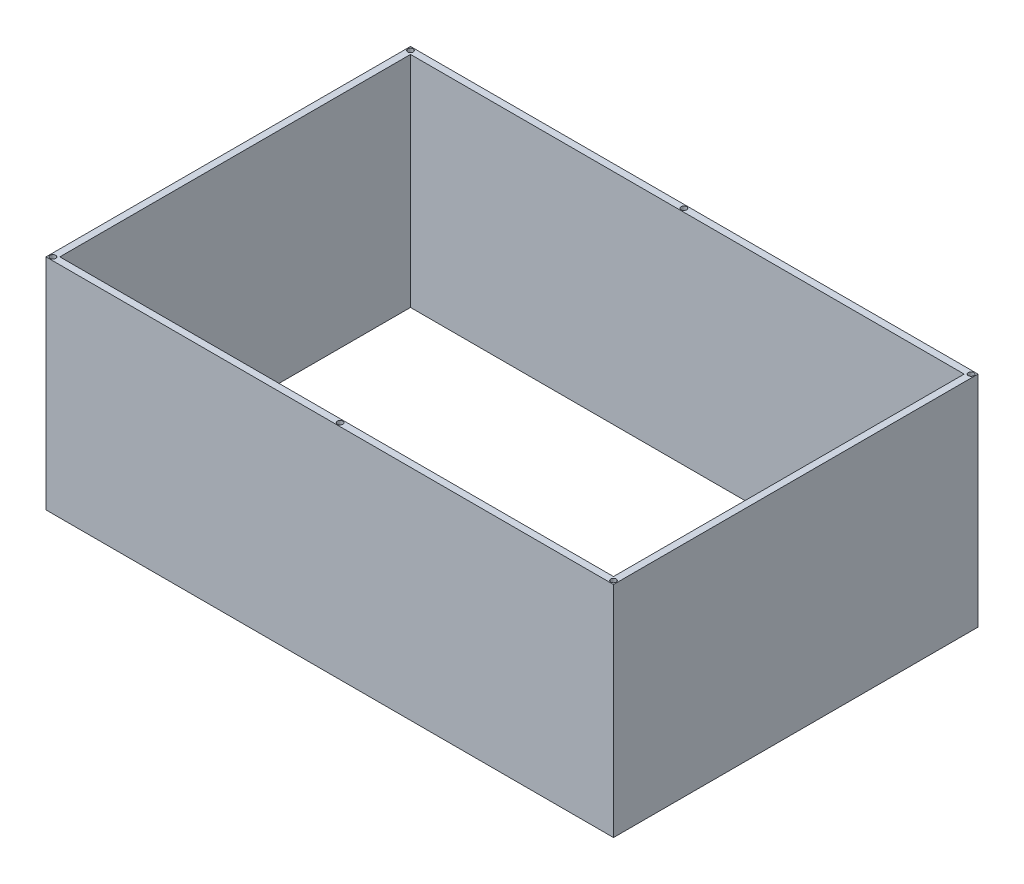
SolidWorks part; units mm, degrees
material "6061-T6 (SS)"
ref_plane "Front Plane" through (0, 0, 0) normal (0, 0, 1) x (1, 0, 0)
ref_plane "Top Plane" through (0, 0, 0) normal (0, 1, 0) x (1, 0, 0)
ref_plane "Right Plane" through (0, 0, 0) normal (1, 0, 0) x (0, 0, -1)
sketch "Sketch5" plane through (0, 0, 0) normal (0, 1, 0) x (1, 0, 0)
  line L0 (-123, 79) -> (-123, -79)
  line L1 (-120, 76) -> (120, 76)
  line L2 (-120, 76) -> (-120, -76)
  line L3 (-120, -76) -> (120, -76)
  line L4 (120, 76) -> (120, -76)
  line L7 (-123, -79) -> (123, -79)
  line L8 (123, 79) -> (123, -79)
  line L9 (-123, 79) -> (123, 79)
  point P0 (0, 0)
  dimension "D1" = 152
  dimension "D2" = 240
  dimension "D3" = 3
extrude "Boss-Extrude1" add sketch "Sketch5" along normal blind 95
hole_wizard "M2 Clearance Hole1" positions "3DSketch1" profile "Sketch8" hole size "M2" standard "DIN"
sketch3d "3DSketch1"
  line L0 (123, 95, -79) -> (-123, 95, -79) construction
  line L1 (-123, 95, -79) -> (-123, 95, 79) construction
  line L2 (123, 95, 79) -> (123, 95, -79) construction
  line L3 (-123, 95, 79) -> (123, 95, 79) construction
  point P0 (-121.5, 95, -77.5)
  point P2 (-121.5, 95, 77.5)
  point P4 (121.5, 95, 77.5)
  point P6 (121.5, 95, -77.5)
  point P8 (-3, 95, -77.5)
  point P10 (3, 95, 77.5)
  dimension "D1" = 1.5
  dimension "D2" = 1.5
  dimension "D3" = 1.5
  dimension "D4" = 1.5
  dimension "D5" = 1.5
  dimension "D6" = 1.5
  dimension "D7" = 1.5
  dimension "D8" = 1.5
  dimension "D9" = 1.5
  dimension "D10" = 1.5
  dimension "D11" = 120
  dimension "D12" = 120
sketch "Sketch8" plane through (-121.5, 95, -77.5) normal (1, 0, 0) x (0, 0, 1)
  line L0 (0, 0) -> (0, 3.721)
  line L1 (0, 3.721) -> (1.2, 3)
  line L2 (1.2, 3) -> (1.2, 0)
  line L5 (1.2, 0) -> (0, 0)
  line L10 (0, 3.721) -> (-1.2, 3) construction
  line L11 (0, -6.35) -> (0, 107.95) construction
  dimension "Hole Dia." = 2.4
  dimension "Hole Depth" = 3
  dimension "Drill Angle" = 118
